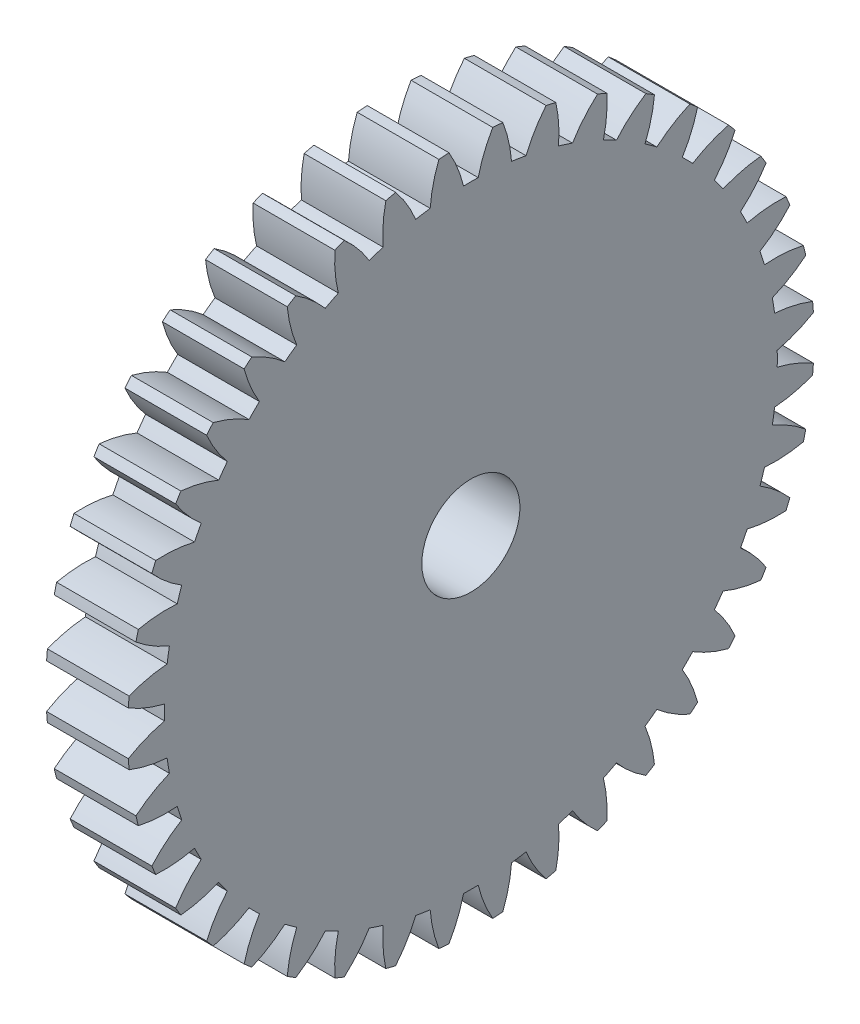
SolidWorks part; units mm, degrees
ref_plane "Plane1" through (0, 0, 0) normal (0, 0, 1) x (1, 0, 0)
ref_plane "Plane2" through (0, 0, 0) normal (0, 1, 0) x (1, 0, 0)
ref_plane "Plane3" through (0, 0, 0) normal (1, 0, 0) x (0, 0, -1)
sketch "HoldingSke" plane through (0, 0, 0) normal (0, 1, 0) x (1, 0, 0)
  line L0 (0, 0) -> (0.766, -0.6428)
  line L1 (-15, 0) -> (100, 0) construction
  line L2 (0, 0) -> (-2.1039, 2.3779)
  line L3 (0, 0) -> (-11.863, 4.5341)
  line L4 (0, 0) -> (6.6156, 5.5511)
  line L5 (0, 0) -> (-10.3065, -3.844)
  line L6 (0, 0) -> (-4.1448, -2.7965)
  line L7 (-2.1039, 2.3779) -> (0.2639, 13.1201)
  line L8 (-76.2, 54.61) -> (-75.2, 54.61)
  line L9 (-71.009, 38.7566) -> (-53.1078, 45.2721)
  line L10 (-76.2, 71.12) -> (104.1128, 71.12)
  line L11 (0, 0) -> (-5, 0)
  line L12 (-76.2, 101.6) -> (-76.162, 101.6)
  line L13 (24.9733, 27.94) -> (52.9518, 28.4284)
  line L14 (24.9733, 27.94) -> (24.9743, 27.94)
  line L15 (24.9733, 27.94) -> (100.4006, 29.5858)
  line L16 (-63.627, -1) -> (-12.827, -1)
  circle A0 centre (0, 0) radius 3
  circle A1 centre (0, 0) radius 7
  circle A2 centre (0, 0) radius 7
  circle A3 centre (0, 0) radius 3
  dimension "MHD" = 14
  dimension "Hub_dia" = 14
  dimension "Bore" = 6
  dimension "MBD" = 6
  dimension "Pitch" = 1
  dimension "Overall_len" = 11
  dimension "Thickness" = 5
  dimension "OAL" = 11.0001
  dimension "T_dim" = 1
  dimension "Ap" = 20
  dimension "H" = 19.05
  dimension "Pitch_radius" = 180.3128
  dimension "Width" = 5
  dimension "Backlash" = 0.038
  dimension "Addendum_fac" = 1
  dimension "Dedendum_fac" = 1.25
  dimension "Clearance_fac" = 0.25
  dimension "Dedendum_add" = 0.001
  dimension "Module" = 1
sketch "BasProSke" plane through (0, 0, 0) normal (0, 1, 0) x (1, 0, 0)
  line L0 (-10, 0) -> (60, 0) construction
  line L1 (0, 0) -> (0, 21)
  line L2 (0, 0) -> (5, 0)
  line L3 (5, 0) -> (5, 21)
  line L4 (5, 21) -> (0, 21)
  dimension "Thickness" = 5
revolve "Base-Revolve" add sketch "BasProSke" angle 360 about L0
sketch "TooCutSke" plane through (0, 0, 0) normal (1, 0, 0) x (0, 0, -1)
  line L1 (0, 0) -> (0, 107) construction
  line L2 (0, 0) -> (-0.8517, 19.9819) construction
  line L3 (0, 0) -> (-3.1363, 39.8509) construction
  line L4 (-0.8517, 19.9819) -> (-1.5682, 19.9255) construction
  arc A0 (0.4487, 18.7436) -> (-0.4487, 18.7436) centre (0, 0) ccw
  arc A1 (1.3547, 20.9817) -> (-1.3547, 20.9817) centre (0, 0) ccw
  circle A2 centre (0, 0) radius 20 construction
  circle A3 centre (0, 0) radius 18.7939 construction
  arc A4 (-0.4487, 18.7436) -> (-1.3547, 20.9817) centre (-8.2322, 16.895) ccw
  arc A5 (1.3547, 20.9817) -> (0.4487, 18.7436) centre (8.2322, 16.895) ccw
  dimension "Half_CT" = 0.7187
extrude "ToothCut" cut sketch "TooCutSke" along normal through all
fillet "Breaks" [suppressed] radius 0.02
fillet "RootFillets" [suppressed] radius 0.251
pattern_circular "TeethCuts" count 40 every 9 about axis through (-10, 0, 0) along (1, 0, 0) of "ToothCut", "RootFillets", "Breaks"
sketch "HubNeaOneSke" plane through (0, 0, 0) normal (-1, 0, 0) x (0, 0, 1)
  circle A0 centre (0, 0) radius 7
  dimension "Diameter" = 14
extrude "HubNearOne" add sketch "HubNeaOneSke" along normal blind 6.0001
sketch "HubNeaBotSke" plane through (0, 0, 0) normal (-1, 0, 0) x (0, 0, 1)
  circle A0 centre (0, 0) radius 7
  dimension "Diameter" = 14
extrude "HubNearBoth" [suppressed] add sketch "HubNeaBotSke" along normal blind 3
ref_plane "FarPln" through (5, 0, 0) normal (1, 0, 0) x (0, 0, -1)
sketch "HubFarSke" plane through (5, 0, 0) normal (1, 0, 0) x (0, 0, -1)
  circle A0 centre (0, 0) radius 7
  dimension "Diameter" = 14
extrude "HubFar" [suppressed] add sketch "HubFarSke" along normal blind 3
sketch "BorSke" plane through (0, 0, 0) normal (1, 0, 0) x (0, 0, -1)
  circle A0 centre (0, 0) radius 3
  dimension "Diameter" = 6
extrude "Bore" cut sketch "BorSke" along normal mid plane 22.0001
sketch "KeySke" plane through (0, 0, 0) normal (1, 0, 0) x (0, 0, -1)
  line L0 (-1, 0) -> (-1, 4)
  line L1 (-1, 4) -> (1, 4)
  line L2 (1, 4) -> (1, 0)
  line L3 (0, 0) -> (0, 34) construction
  line L4 (-1, 0) -> (1, 0)
  dimension "Offset" = 4
  dimension "Width" = 2
extrude "Keyway" [suppressed] cut sketch "KeySke" along normal mid plane 22.0001
pattern_circular "Keyway2" [suppressed] count 2 every 90 about axis through (-10, 0, 0) along (1, 0, 0)
equation "' \"Module@HoldingSke\" = 6.35"
equation "' \"Num_teeth@HoldingSke\" = 12"
equation "' \"Ap@HoldingSke\" =  20"
equation "' \"Ap@HoldingSke\" = 20"
equation "' \"Width@HoldingSke\" = 0.5 * 25.4"
equation "' \"Hub_dia@HoldingSke\"= 1 * 25.4"
equation "' \"Hub_dia@HoldingSke\" = 1 * 25.4"
equation "' \"Overall_len@HoldingSke\" = 1.0 * 25.4"
equation "' \"Bore@HoldingSke\" = 0.75 * 25.4"
equation "' \"T_dim@HoldingSke\" = 0.1 * 25.4"
equation "' \"Width@KeySke\" = 0.25 * 25.4"
equation "' \"Show_teeth@HoldingSke\" = 13"
equation "' \"Backlash@HoldingSke\" = 0.009 * 25.4"
equation "' \"Addendum_fac@HoldingSke\" = 1.0"
equation "' \"Dedendum_fac@HoldingSke\" = 1.25"
equation "' \"Dedendum_add@HoldingSke\" = 0.00005 * 25.4"
equation "' \"Clearance_fac@HoldingSke\" = 0.25"
equation "\"Pitch@HoldingSke\" = 1 / \"Module@HoldingSke\""
equation "\"Overcut_dia@TooCutSke\" = (\"Num_teeth@HoldingSke\" + 2 * \"Addendum_fac@HoldingSke\") / \"Pitch@HoldingSke\" + 0.002 * 25.4"
equation "\"Pitch_dia@TooCutSke\" = \"Num_teeth@HoldingSke\" / \"Pitch@HoldingSke\""
equation "\"Base_dia@TooCutSke\" = \"Num_teeth@HoldingSke\" / \"Pitch@HoldingSke\" * cos((\"Ap@HoldingSke\"  * 3.14159265 / 180))"
equation "\"Root_dia@TooCutSke\" = (\"Num_teeth@HoldingSke\" + 2) / \"Pitch@HoldingSke\" - 2 * (\"Addendum_fac@HoldingSke\" + \"Dedendum_fac@HoldingSke\") / \"Pitch@HoldingSke\" - \"Dedendum_add@HoldingSke\" * 2"
equation "\"Half_ang@TooCutSke\" = 180 / \"Num_teeth@HoldingSke\""
equation "\"Half_CT@TooCutSke\" = \"Num_teeth@HoldingSke\" / \"Pitch@HoldingSke\" * sin((3.14159265 / 2 / \"Num_teeth@HoldingSke\")) / 2 - 7 * \"Backlash@HoldingSke\" / 4"
equation "\"Flank_rad@TooCutSke\" = \"Num_teeth@HoldingSke\" / \"Pitch@HoldingSke\" / 5"
equation "\"Radius@RootFillets\" = \"Clearance_fac@HoldingSke\" / \"Pitch@HoldingSke\" + \"Dedendum_add@HoldingSke\""
equation "\"Break_rad@Breaks\" = 0.02 / \"Pitch@HoldingSke\""
equation "\"Thickness@HoldingSke\" = \"Width@HoldingSke\""
equation "\"OAL@HoldingSke\" = \"Thickness@HoldingSke\""
equation "\"MHD@HoldingSke\" = (\"Num_teeth@HoldingSke\" + 2) / \"Pitch@HoldingSke\" - 2 * (\"Addendum_fac@HoldingSke\" + \"Dedendum_fac@HoldingSke\")  / \"Pitch@HoldingSke\" - \"Dedendum_add@HoldingSke\" * 2"
equation "\"MBD@HoldingSke\" = (\"Num_teeth@HoldingSke\" + 2) / \"Pitch@HoldingSke\" - 2 * (\"Addendum_fac@HoldingSke\" + \"Dedendum_fac@HoldingSke\")  / \"Pitch@HoldingSke\" - \"Dedendum_add@HoldingSke\" * 2 - 0.002 * 25.4"
equation "\"MHD@HoldingSke\" = ((sgn( \"MHD@HoldingSke\" - \"Hub_dia@HoldingSke\" )-1)*( \"MHD@HoldingSke\" - \"Hub_dia@HoldingSke\" ))/-2+ \"Hub_dia@HoldingSke\""
equation "\"MBD@HoldingSke\" = ((sgn( \"MBD@HoldingSke\" - \"Bore@HoldingSke\" )-1)*( \"MBD@HoldingSke\" - \"Bore@HoldingSke\" ))/-2+ \"Bore@HoldingSke\""
equation "\"OAL@HoldingSke\" = ((sgn( \"OAL@HoldingSke\" - \"Overall_len@HoldingSke\" )+1)*( \"OAL@HoldingSke\" - \"Overall_len@HoldingSke\" ))/2 + \"Overall_len@HoldingSke\" + 0.000002 * 25.4"
equation "\"Num_teeth@TeethCuts\" = int( \"Show_teeth@HoldingSke\" ) + 1"
equation "\"Num_teeth@TeethCuts\" = ((sgn( \"Num_teeth@TeethCuts\" - \"Num_teeth@HoldingSke\" )-1)*( \"Num_teeth@TeethCuts\" - \"Num_teeth@HoldingSke\" ))/-2+ \"Num_teeth@HoldingSke\""
equation "\"Num_teeth@TeethCuts\" = ((sgn( \"Num_teeth@TeethCuts\" - 2.0)+1)*( \"Num_teeth@TeethCuts\" - 2.0))/2 +2.0"
equation "\"Angle@TeethCuts\" = 360.0 / \"Num_teeth@HoldingSke\""
equation "\"Diameter@BasProSke\" = (\"Num_teeth@HoldingSke\" + 2 * \"Addendum_fac@HoldingSke\") / \"Pitch@HoldingSke\""
equation "\"Thickness@BasProSke\"  = \"Thickness@HoldingSke\""
equation "' \"Fillet_rad@BasProSke\" =  \"Thickness@HoldingSke\" * 0.05"
equation "' \"Fillet_rad@BasProSke\" = \"Thickness@HoldingSke\" * 0.05"
equation "\"MHD@HoldingSke\" = ((sgn( \"MHD@HoldingSke\" - \"Root_dia@TooCutSke\" )-1)*( \"MHD@HoldingSke\" - \"Root_dia@TooCutSke\" ))/-2+ \"Root_dia@TooCutSke\""
equation "\"Diameter@HubNeaOneSke\" = \"MHD@HoldingSke\""
equation "\"Length@HubNearOne\" = \"OAL@HoldingSke\" - \"Thickness@BasProSke\""
equation "\"Diameter@HubNeaBotSke\" = \"MHD@HoldingSke\""
equation "\"Length@HubNearBoth\" = ( \"OAL@HoldingSke\" - \"Thickness@BasProSke\" ) / 2.0"
equation "\"Thickness@FarPln\" = \"Thickness@BasProSke\""
equation "\"Diameter@HubFarSke\" = \"MHD@HoldingSke\""
equation "\"Length@HubFar\" = ( \"OAL@HoldingSke\" - \"Thickness@BasProSke\" ) / 2.0"
equation "\"Diameter@BorSke\" = \"MBD@HoldingSke\""
equation "\"D1@Bore\" = \"OAL@HoldingSke\" * 2.0"
equation "\"D1@Keyway\" = \"OAL@HoldingSke\" * 2.0"
equation "\"Offset@KeySke\" = \"T_dim@HoldingSke\" + \"MBD@HoldingSke\" / 2.0"
